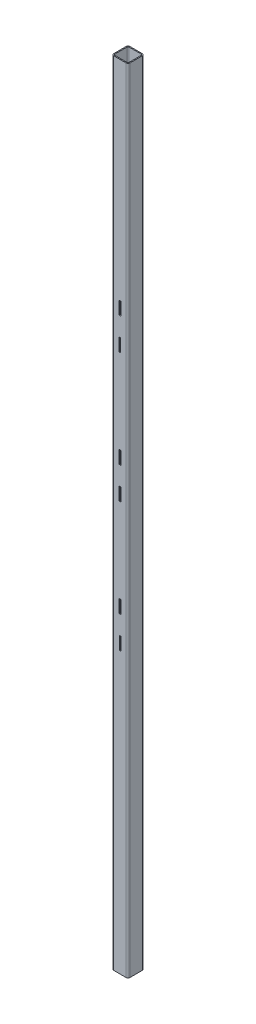
SolidWorks part; units mm, degrees
ref_plane "Спереди" through (0, 0, 0) normal (0, 0, 1) x (1, 0, 0)
ref_plane "Сверху" through (0, 0, 0) normal (0, 1, 0) x (1, 0, 0)
ref_plane "Справа" through (0, 0, 0) normal (1, 0, 0) x (0, 0, -1)
sketch "Эскиз1" plane through (0, 0, 0) normal (0, 0, 1) x (1, 0, 0)
  line L0 (0, 0) -> (0, 1220)
  line L1 (-254.7356, 610) -> (254.7356, 610) construction
  point P5 (0, 610)
  dimension "D1" = 1220
ref_plane "Плоскость2" through (0, 610, 0) normal (0, 1, 0) x (1, 0, 0)
other "Square tube - configured 20 X 20 X 2(1)"
ref_plane "Плоскость1" through (0, 0, 0) normal (0, 1, 0) x (-1, 0, 0)
sketch "Sketch1" plane through (0, 0, 0) normal (0, 1, 0) x (-1, 0, 0)
  line L0 (-9.5, -11) -> (9.5, -11)
  line L1 (-11, -9.5) -> (-11, 9.5)
  line L2 (9.5, 11) -> (-9.5, 11)
  line L3 (11, 9.5) -> (11, -9.5)
  line L4 (-9.5, -12.5) -> (9.5, -12.5)
  line L5 (-12.5, -9.5) -> (-12.5, 9.5)
  line L6 (9.5, 12.5) -> (-9.5, 12.5)
  line L7 (12.5, 9.5) -> (12.5, -9.5)
  arc A0 (12.5, 9.5) -> (9.5, 12.5) centre (9.5, 9.5) ccw
  arc A1 (9.5, -12.5) -> (12.5, -9.5) centre (9.5, -9.5) ccw
  arc A2 (-12.5, -9.5) -> (-9.5, -12.5) centre (-9.5, -9.5) ccw
  arc A3 (-9.5, 12.5) -> (-12.5, 9.5) centre (-9.5, 9.5) ccw
  arc A4 (-9.5, 11) -> (-11, 9.5) centre (-9.5, 9.5) ccw
  arc A5 (11, 9.5) -> (9.5, 11) centre (9.5, 9.5) ccw
  arc A6 (9.5, -11) -> (11, -9.5) centre (9.5, -9.5) ccw
  arc A7 (-11, -9.5) -> (-9.5, -11) centre (-9.5, -9.5) ccw
  point P0 (-12.5, 0)
  point P1 (12.5, 0)
  point P2 (0, 12.5)
  point P3 (0, -12.5)
  point P4 (0, 0)
  point P5 (-12.5, -12.5)
  point P6 (12.5, -12.5)
  point P7 (12.5, 12.5)
  point P8 (-12.5, 12.5)
  point P33 (0, 0)
  dimension "D1" = 3
  dimension "Thickness" = 1.5
  dimension "V_leg" = 25
sketch "Эскиз2" plane through (-12.5, 0, 0) normal (-1, 0, 0) x (0, 0, 1)
  circle A1 centre (0, 17) radius 3.75
  circle A2 centre (0, 17) radius 3.75
  circle A3 centre (0, 47) radius 3.75
  circle A4 centre (0, 47) radius 3.75
  dimension "D1" = 0
  dimension "D2" = 0
extrude "Вырез-Вытянуть1" cut sketch "Эскиз2" against normal up to next
mirror "Зеркальное отражение1" about plane through (0, 610, 0) normal (0, 1, 0) of "Вырез-Вытянуть1"
sketch "Эскиз3" plane through (0, 0, 12.5) normal (0, 0, 1) x (1, 0, 0)
  line L0 (0, 1220) -> (0, 0) construction
  line L1 (-9.5, 1220) -> (9.5, 1220) construction
  line L2 (-1.25, 829.2206) -> (-1.25, 699.264) construction
  line L7 (-1, 630.264) -> (-1, 500.3075) construction
  line B0 (-1.5, 898.2206) -> (1.5, 898.2206)
  line B1 (-1.5, 898.2206) -> (-1.5, 878.2206)
  line B2 (-1.5, 878.2206) -> (1.5, 878.2206)
  line B3 (1.5, 898.2206) -> (1.5, 878.2206)
  line B4 (0, 878.2206) -> (0, 898.2206) construction
  line B5 (-1.5, 888.2206) -> (1.5, 888.2206) construction
  line B6 (-1.25, 849.2206) -> (1.25, 849.2206)
  line B7 (-1.25, 849.2206) -> (-1.25, 829.2206)
  line B8 (-1.25, 829.2206) -> (1.25, 829.2206)
  line B9 (1.25, 849.2206) -> (1.25, 829.2206)
  line B10 (0, 829.2206) -> (0, 849.2206) construction
  line B11 (-1.25, 839.2206) -> (1.25, 839.2206) construction
  line B12 (-1.25, 699.264) -> (1.75, 699.264)
  line B13 (-1.25, 699.264) -> (-1.25, 679.264)
  line B14 (-1.25, 679.264) -> (1.75, 679.264)
  line B15 (1.75, 699.264) -> (1.75, 679.264)
  line B16 (-1, 650.264) -> (1.5, 650.264)
  line B17 (-1, 650.264) -> (-1, 630.264)
  line B18 (-1, 630.264) -> (1.5, 630.264)
  line B19 (1.5, 650.264) -> (1.5, 630.264)
  line B20 (-1, 500.3075) -> (2, 500.3075)
  line B21 (-1, 500.3075) -> (-1, 480.3075)
  line B22 (-1, 480.3075) -> (2, 480.3075)
  line B23 (2, 500.3075) -> (2, 480.3075)
  line B24 (-0.75, 451.3075) -> (1.75, 451.3075)
  line B25 (-0.75, 451.3075) -> (-0.75, 431.3075)
  line B26 (-0.75, 431.3075) -> (1.75, 431.3075)
  line B27 (1.75, 451.3075) -> (1.75, 431.3075)
sketch_block_instance "Блок1-1"
sketch_block "Блок1" parameters "D1"=3, "D2"=20, "D3"=49
sketch_block_instance "Блок1-2"
sketch_block_instance "Блок1-3"
extrude "Вырез-Вытянуть2" cut sketch "Эскиз3" against normal through all
